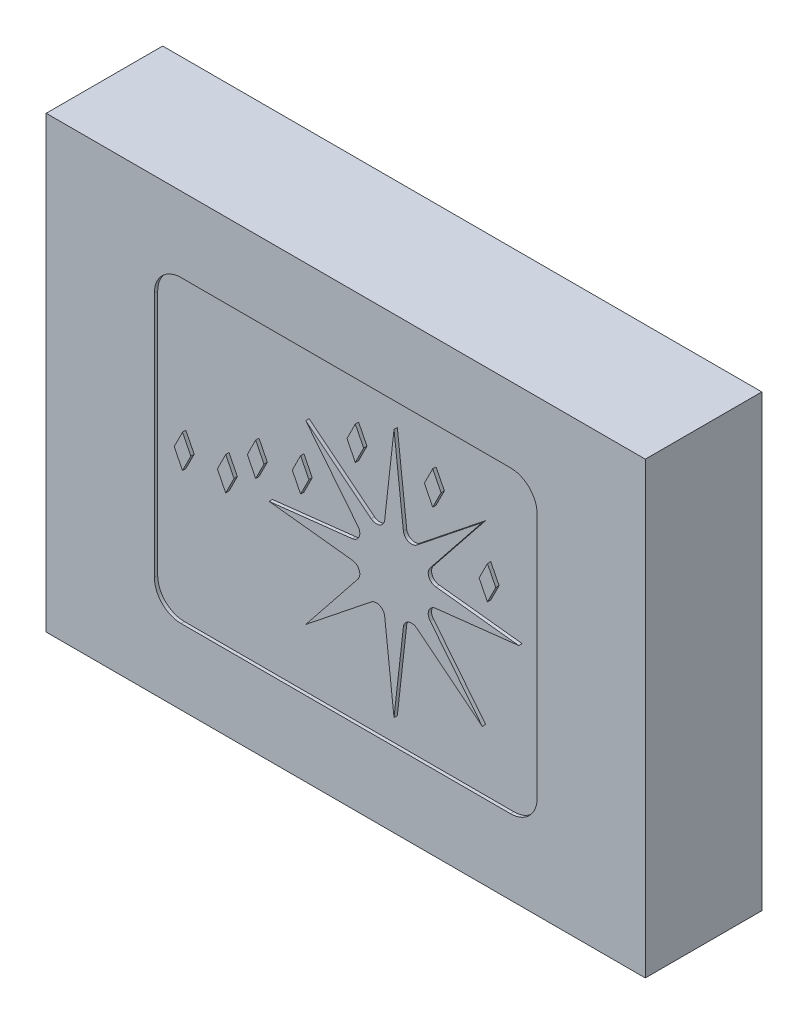
SolidWorks part; units mm, degrees
ref_plane "Front" through (0, 0, 0) normal (0, 0, 1) x (1, 0, 0)
ref_plane "Top" through (0, 0, 0) normal (0, 1, 0) x (1, 0, 0)
ref_plane "Right" through (0, 0, 0) normal (1, 0, 0) x (0, 0, -1)
sketch "Sketch1" plane through (0, 0, 0) normal (0, 0, 1) x (1, 0, 0)
  line L1 (-18, -13.5) -> (18, -13.5)
  line L2 (-18, -13.5) -> (-18, 13.5)
  line L3 (-18, 13.5) -> (18, 13.5)
  line L4 (18, -13.5) -> (18, 13.5)
  line L5 (-18, -13.5) -> (18, 13.5) construction
  line L6 (-18, 13.5) -> (18, -13.5) construction
  point P0 (0, 0)
  dimension "D1" = 36
  dimension "D2" = 27
extrude "Boss-Extrude1" add sketch "Sketch1" along normal blind 7
sketch "Sketch2" plane through (0, 0, 7) normal (0, 0, 1) x (1, 0, 0)
  line L1 (-9.9, -9) -> (9.9, -9)
  line L2 (-11.5, -7.4) -> (-11.5, 7.4)
  line L3 (-9.9, 9) -> (9.9, 9)
  line L4 (11.5, -7.4) -> (11.5, 7.4)
  line L5 (-11.5, -9) -> (11.5, 9) construction
  line L6 (-11.5, 9) -> (11.5, -9) construction
  arc A0 (-9.9, -9) -> (-11.5, -7.4) centre (-9.9, -7.4) cw
  arc A1 (9.9, -9) -> (11.5, -7.4) centre (9.9, -7.4) ccw
  arc A2 (9.9, 9) -> (11.5, 7.4) centre (9.9, 7.4) cw
  arc A3 (-11.5, 7.4) -> (-9.9, 9) centre (-9.9, 7.4) cw
  point P0 (0, 0)
  dimension "D3" = 1.6
  dimension "D1" = 18
  dimension "D2" = 23
extrude "Cut-Extrude1" cut sketch "Sketch2" against normal blind 0.2
sketch "Sketch3" plane through (0, 0, 6.8) normal (0, 0, 1) x (1, 0, 0)
  line L0 (2.9, 0) -> (2.9, 7.5) construction
  line L1 (2.9, 0) -> (10.4, 0) construction
  line L2 (2.9, 0) -> (8.2033, 5.3033) construction
  line L3 (2.9, 0) -> (5.7701, 6.9291) construction
  line L4 (2.9, 0) -> (9.8291, 2.8701) construction
  line L5 (2.9, 7.5) -> (3.4617, 2.4997)
  line L6 (4.2704, 2.1647) -> (8.2033, 5.3033)
  line L7 (8.2033, 5.3033) -> (5.0647, 1.3704)
  line L8 (5.3997, 0.5617) -> (10.4, 0)
  line L9 (5.3997, -0.5617) -> (10.4, 0)
  line L10 (8.2033, -5.3033) -> (5.0647, -1.3704)
  line L11 (4.2704, -2.1647) -> (8.2033, -5.3033)
  line L12 (2.9, -7.5) -> (3.4617, -2.4997)
  line L13 (2.9, 7.5) -> (2.3383, 2.4997)
  line L14 (1.5296, 2.1647) -> (-2.4033, 5.3033)
  line L15 (-2.4033, 5.3033) -> (0.7353, 1.3704)
  line L16 (0.4003, 0.5617) -> (-4.6, 0)
  line L17 (0.4003, -0.5617) -> (-4.6, 0)
  line L18 (-2.4033, -5.3033) -> (0.7353, -1.3704)
  line L19 (1.5296, -2.1647) -> (-2.4033, -5.3033)
  line L20 (2.9, -7.5) -> (2.3383, -2.4997)
  line L21 (9.9, 9) -> (-9.9, 9) construction
  line L22 (11.5, -7.4) -> (11.5, 7.4) construction
  circle A0 centre (2.9, 0) radius 7.5 construction
  circle A1 centre (2.9, 0) radius 1.7318 construction
  arc A2 (5.0647, 1.3704) -> (5.3997, 0.5617) centre (5.4556, 1.0585) ccw
  arc A3 (3.4617, 2.4997) -> (4.2704, 2.1647) centre (3.9585, 2.5556) ccw
  arc A4 (5.0647, -1.3704) -> (5.3997, -0.5617) centre (5.4556, -1.0585) cw
  arc A5 (3.4617, -2.4997) -> (4.2704, -2.1647) centre (3.9585, -2.5556) cw
  arc A6 (2.3383, 2.4997) -> (1.5296, 2.1647) centre (1.8415, 2.5556) cw
  arc A7 (0.7353, 1.3704) -> (0.4003, 0.5617) centre (0.3444, 1.0585) cw
  arc A8 (0.7353, -1.3704) -> (0.4003, -0.5617) centre (0.3444, -1.0585) ccw
  arc A9 (2.3383, -2.4997) -> (1.5296, -2.1647) centre (1.8415, -2.5556) ccw
  point P12 (4.5, 0.6627)
  point P15 (3.5627, 1.6)
  dimension "D1" = 15
  dimension "D5" = 0.5
  dimension "D6" = 9
  dimension "D7" = 8.6
  dimension "D2" = 45
  dimension "D3" = 22.5
  dimension "D4" = 22.5
  dimension "D8" = 12.818
extrude "Boss-Extrude2" add sketch "Sketch3" along normal blind 0.2
sketch "Sketch5" plane through (0, 0, 6.8) normal (0, 0, 1) x (1, 0, 0)
  line L0 (-5.4134, 2.7851) -> (-5.4134, 0.7851) construction
  line L1 (-4.9134, 1.7851) -> (-5.9134, 1.7851) construction
  line L2 (-5.4134, 2.7851) -> (-4.9134, 1.7851)
  line L3 (-4.9134, 1.7851) -> (-5.4134, 0.7851)
  line L4 (-5.4134, 0.7851) -> (-5.9134, 1.7851)
  line L5 (-5.9134, 1.7851) -> (-5.4134, 2.7851)
  line L6 (-5.4134, 3.8851) -> (-5.8994, 3.8851) construction
  line L7 (8.5134, 3.3251) -> (8.5134, 1.3251) construction
  line L8 (8.5134, 3.3251) -> (9.0134, 2.3251)
  line L9 (8.0134, 2.3251) -> (8.5134, 3.3251)
  line L10 (9.0134, 2.3251) -> (8.0134, 2.3251) construction
  line L11 (8.5134, 4.4251) -> (10.1027, 4.4251) construction
  line L12 (9.0134, 2.3251) -> (8.5134, 1.3251)
  line L13 (8.5134, 1.3251) -> (8.0134, 2.3251)
  line L14 (10.4, 0) -> (5.3997, 0.5617) construction
  line L15 (5.0647, 1.3704) -> (8.2033, 5.3033) construction
  line L16 (5.7251, 5.6134) -> (4.7251, 5.6134) construction
  line L17 (4.7251, 5.6134) -> (5.2251, 6.6134)
  line L18 (5.2251, 6.6134) -> (5.7251, 5.6134)
  line L19 (5.2251, 4.6134) -> (4.7251, 5.6134)
  line L20 (5.2251, 6.6134) -> (5.2251, 4.6134) construction
  line L21 (5.7251, 5.6134) -> (5.2251, 4.6134)
  line L22 (5.2251, 7.7134) -> (5.8963, 7.7134) construction
  line L23 (0.5749, 6.6134) -> (0.5749, 4.6134) construction
  line L24 (0.5749, 6.6134) -> (1.0749, 5.6134)
  line L25 (0.5749, 7.7134) -> (1.4655, 7.7134) construction
  line L26 (0.0749, 5.6134) -> (0.5749, 6.6134)
  line L27 (1.0749, 5.6134) -> (0.5749, 4.6134)
  line L28 (1.0749, 5.6134) -> (0.0749, 5.6134) construction
  line L29 (0.5749, 4.6134) -> (0.0749, 5.6134)
  line L30 (-2.7134, 3.3251) -> (-2.7134, 1.3251) construction
  line L31 (-2.7134, 3.3251) -> (-2.2134, 2.3251)
  line L32 (-2.7134, 4.4251) -> (-1.9389, 4.4251) construction
  line L33 (-3.2134, 2.3251) -> (-2.7134, 3.3251)
  line L34 (-2.2134, 2.3251) -> (-2.7134, 1.3251)
  line L35 (-2.2134, 2.3251) -> (-3.2134, 2.3251) construction
  line L36 (-2.7134, 1.3251) -> (-3.2134, 2.3251)
  line L37 (-6.7134, 0.1359) -> (-7.7134, 0.1359) construction
  line L38 (-7.2134, 1.1359) -> (-6.7134, 0.1359)
  line L39 (-7.2134, -0.8641) -> (-7.7134, 0.1359)
  line L40 (-7.2134, 1.1359) -> (-7.2134, -0.8641) construction
  line L41 (-6.7134, 0.1359) -> (-7.2134, -0.8641)
  line L42 (-7.2134, 2.2359) -> (-8.8778, 2.2359) construction
  line L43 (-7.7134, 0.1359) -> (-7.2134, 1.1359)
  line L44 (-9.809, 1) -> (-9.809, -1) construction
  line L45 (-9.809, 1) -> (-9.309, 0)
  line L46 (-9.809, 2.1) -> (-12.117, 2.1) construction
  line L47 (-10.309, 0) -> (-9.809, 1)
  line L48 (-9.309, 0) -> (-9.809, -1)
  line L49 (-9.309, 0) -> (-10.309, 0) construction
  line L50 (-9.809, -1) -> (-10.309, 0)
  line L51 (8.2033, 5.3033) -> (4.2704, 2.1647) construction
  line L52 (9.9, 9) -> (-9.9, 9) construction
  line L53 (3.4617, 2.4997) -> (2.9, 7.5) construction
  line L54 (2.9, 7.5) -> (2.3383, 2.4997) construction
  line L55 (1.5296, 2.1647) -> (-2.4033, 5.3033) construction
  line L56 (-2.4033, 5.3033) -> (0.7353, 1.3704) construction
  line L57 (0.4003, 0.5617) -> (-4.6, 0) construction
  line L58 (-4.6, 0) -> (-5.4098, 0.7445) construction
  circle A0 centre (-5.4134, 1.7851) radius 2.1 construction
  circle A1 centre (8.5134, 2.3251) radius 2.1 construction
  circle A2 centre (5.2251, 5.6134) radius 2.1 construction
  circle A3 centre (0.5749, 5.6134) radius 2.1 construction
  circle A4 centre (-2.7134, 2.3251) radius 2.1 construction
  circle A5 centre (-7.2134, 0.1359) radius 2.1 construction
  circle A6 centre (-9.809, 0) radius 2.1 construction
  circle A7 centre (-5.0049, 0.3723) radius 0.55 construction
  point P4 (-5.4134, 1.7851)
  point P13 (8.5134, 2.3251)
  point P26 (5.2251, 5.6134)
  point P35 (0.5749, 5.6134)
  point P44 (-2.7134, 2.3251)
  point P53 (-7.2134, 0.1359)
  point P62 (-9.809, 0)
  dimension "D25" = 1.1
  dimension "D1" = 2.1
  dimension "D2" = 2
  dimension "D3" = 1
  dimension "D4" = 2
  dimension "D5" = 1
  dimension "D6" = 2.1
  dimension "D7" = 2
  dimension "D8" = 1
  dimension "D9" = 2.1
  dimension "D10" = 2
  dimension "D11" = 1
  dimension "D12" = 2.1
  dimension "D13" = 2
  dimension "D14" = 1
  dimension "D15" = 2.1
  dimension "D16" = 2
  dimension "D17" = 1
  dimension "D18" = 2.1
  dimension "D19" = 2
  dimension "D20" = 1
  dimension "D21" = 2.1
  dimension "D22" = 9
  dimension "D23" = 2.7
  dimension "D24" = 0.54
  dimension "D26" = 1.8
extrude "Boss-Extrude3" add sketch "Sketch5" along normal blind 0.2
